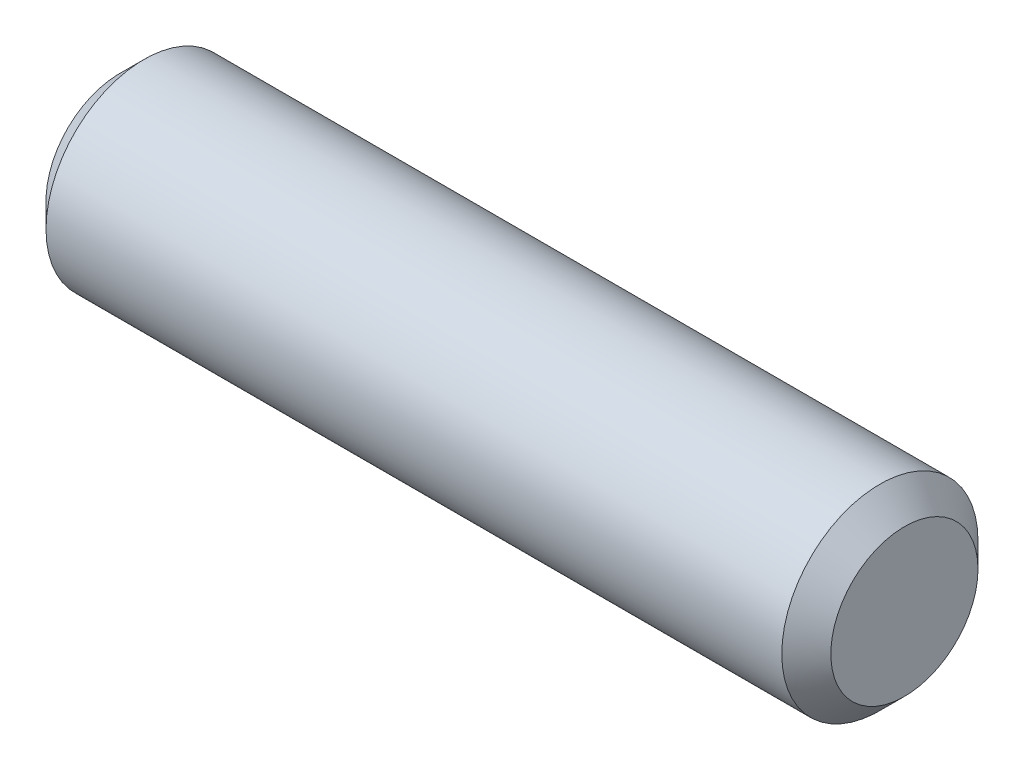
SolidWorks part; units mm, degrees
ref_plane "前视基准面" through (0, 0, 0) normal (0, 0, 1) x (1, 0, 0)
ref_plane "上视基准面" through (0, 0, 0) normal (0, 1, 0) x (1, 0, 0)
ref_plane "右视基准面" through (0, 0, 0) normal (1, 0, 0) x (0, 0, -1)
sketch "草图1" plane through (0, 0, 0) normal (1, 0, 0) x (0, 0, -1)
  circle A0 centre (0, 0) radius 4
  dimension "D1" = 8
extrude "凸台-拉伸1" add sketch "草图1" along normal mid plane 32
chamfer "倒角1" distance 1 angle 45 2 edges at (16, 0, -4) (-16, 0, -4)
